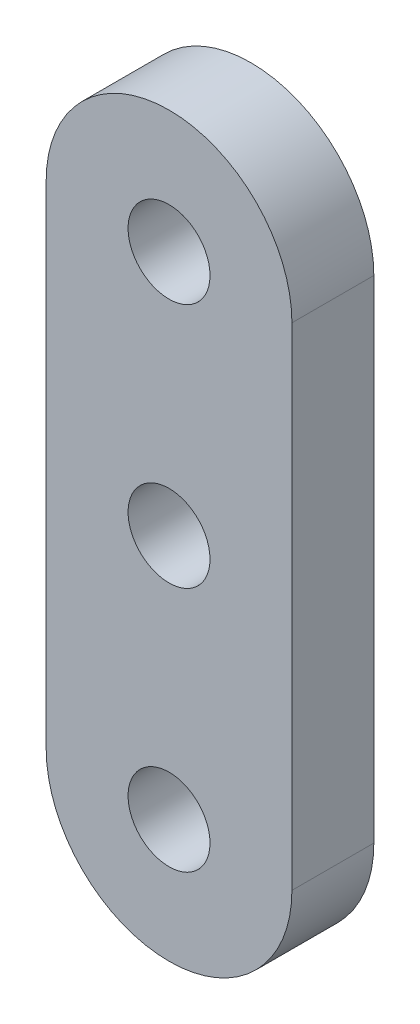
SolidWorks part; units mm, degrees
ref_plane "Alzado" through (0, 0, 0) normal (0, 0, 1) x (1, 0, 0)
ref_plane "Planta" through (0, 0, 0) normal (0, 1, 0) x (1, 0, 0)
ref_plane "Vista lateral" through (0, 0, 0) normal (1, 0, 0) x (0, 0, -1)
sketch "Model" plane through (0, 0, 0) normal (0, 0, 1) x (1, 0, 0)
  line L0 (213.2508, 152.4285) -> (213.2508, 170.4285)
  line L1 (204.2508, 170.4285) -> (204.2508, 152.4285)
  circle A0 centre (208.7508, 152.4285) radius 1.5
  circle A1 centre (208.7508, 161.4285) radius 1.5
  circle A2 centre (208.7508, 170.4285) radius 1.5
  arc A3 (204.2508, 152.4285) -> (213.2508, 152.4285) centre (208.7508, 152.4285) ccw
  arc A4 (213.2508, 170.4285) -> (204.2508, 170.4285) centre (208.7508, 170.4285) ccw
extrude "Saliente-Extruir1" add sketch "Model" along normal blind 3
